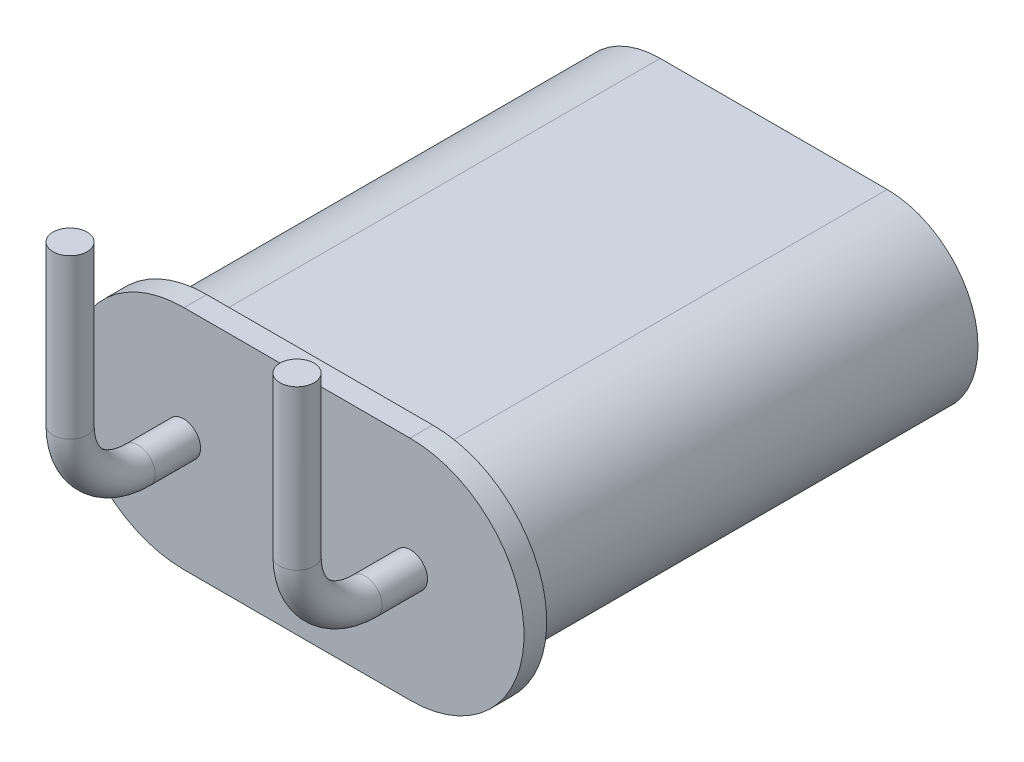
SolidWorks part; units mm, degrees
ref_plane "前视基准面" through (0, 0, 0) normal (0, 0, 1) x (1, 0, 0)
ref_plane "上视基准面" through (0, 0, 0) normal (0, 1, 0) x (1, 0, 0)
ref_plane "右视基准面" through (0, 0, 0) normal (1, 0, 0) x (0, 0, -1)
sketch "草图1" plane through (0, 0, 0) normal (0, 0, 1) x (1, 0, 0)
  line L1 (-9.1238, 3.3374) -> (10.8762, 3.3374)
  line L3 (-9.1238, -12.6626) -> (10.8762, -12.6626)
  arc A0 (10.8762, 3.3374) -> (10.8762, -12.6626) centre (10.8762, -4.6626) cw
  arc A1 (-9.1238, 3.3374) -> (-9.1238, -12.6626) centre (-9.1238, -4.6626) ccw
  point P6 (0, 0)
  point P7 (0, 0)
  dimension "D3" = 8
  dimension "D1" = 20
  dimension "D2" = 16
extrude "凸台-拉伸1" add sketch "草图1" along normal blind 40
sketch "草图4" plane through (0, 0, 40) normal (0, 0, 1) x (1, 0, 0)
  line L0 (0.8762, 10.9713) -> (0.8762, -23.5581) construction
  line L1 (-9.079, 5.3373) -> (10.8313, 5.3373)
  line L2 (-9.1687, -14.6625) -> (10.921, -14.6625)
  arc A0 (-9.1687, -14.6625) -> (-9.079, 5.3373) centre (-9.1238, -4.6626) cw
  arc A1 (-9.1238, 3.3374) -> (-9.1238, -12.6626) centre (-9.1238, -4.6626) ccw construction
  arc A2 (10.921, -14.6625) -> (10.8313, 5.3373) centre (10.8762, -4.6626) ccw
  point P4 (0, 0)
  point P6 (0, 0)
  point P7 (0, 0)
  point P13 (0, 0)
  point P15 (0.8762, -14.6625)
  point P16 (0.8762, 5.3373)
  dimension "D1" = 10
extrude "凸台-拉伸3" add sketch "草图4" along normal blind 2
sketch "草图5" plane through (0, 0, 42) normal (0, 0, 1) x (1, 0, 0)
  circle A0 centre (-9.1238, -4.6626) radius 1.5
  arc A1 (-9.079, 5.3373) -> (-9.1687, -14.6625) centre (-9.1238, -4.6626) ccw construction
  point P3 (0, 0)
ref_plane "基准面1" through (-9.1238, 0, 0) normal (1, 0, 0) x (0, 0, -1)
sketch "草图6" plane through (-9.1238, 0, 0) normal (1, 0, 0) x (0, 0, -1)
  line L0 (-42, -4.6626) -> (-46, -4.6626)
  line L1 (-42, -3.1626) -> (-42, -6.1626) construction
  line L2 (-52, 1.3374) -> (-52, 15.3374)
  arc A0 (-46, -4.6626) -> (-52, 1.3374) centre (-46, 1.3374) cw
  point P7 (-52, -4.6626)
  dimension "D3" = 6
  dimension "D1" = 10
  dimension "D2" = 20
sweep "扫描1" add profiles "草图5" path "草图6"
pattern_linear "阵列(线性)1" count 2 spacing 20 along (1, 0, 0) of "扫描1"
sketch "草图8" plane through (0, -12.6626, 0) normal (0, -1, 0) x (1, 0, 0)
  text T0 "600pf"
extrude "凸台-拉伸5" add sketch "草图8" along normal blind 1
